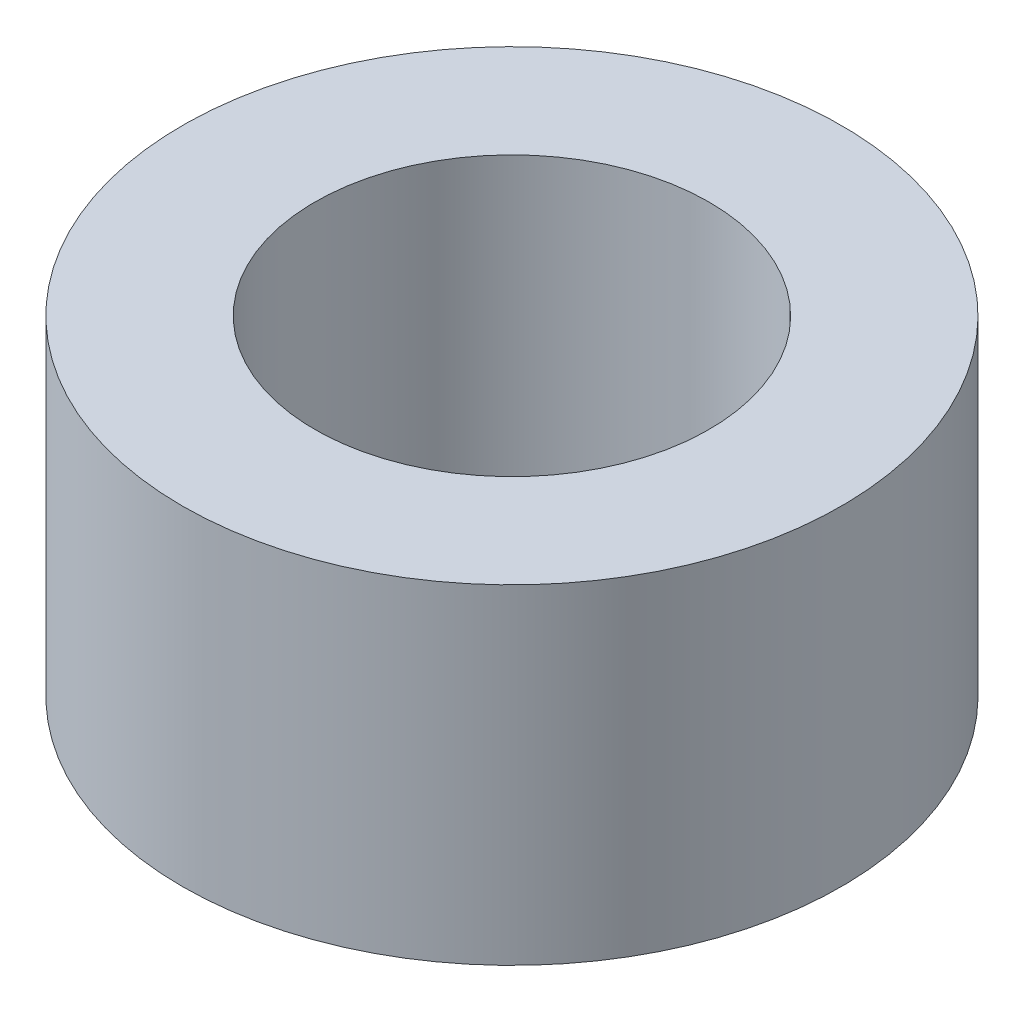
SolidWorks part; units mm, degrees
material "Nylon 101"
ref_plane "Front" through (0, 0, 0) normal (0, 0, 1) x (1, 0, 0)
ref_plane "Top" through (0, 0, 0) normal (0, 1, 0) x (1, 0, 0)
ref_plane "Right" through (0, 0, 0) normal (1, 0, 0) x (0, 0, -1)
sketch "Sketch1" plane through (0, 0, 0) normal (0, 1, 0) x (1, 0, 0)
  circle A0 centre (0, 0) radius 3.175
  dimension "D1" = 6.35
extrude "Boss-Extrude1" add sketch "Sketch1" along normal blind 3.175
sketch "Sketch3" plane through (0, 0, 0) normal (0, -1, 0) x (1, 0, 0)
  point P0 (0, 0)
hole_wizard "#6 Clearance Hole1" positions "3DSketch1" profile "Sketch4" hole size "#6" standard "ANSI Inch" end condition through all
sketch3d "3DSketch1"
  point P0 (0, 0, 0)
  point P4 (0, 0, 0)
sketch "Sketch4" plane through (0, 0, 0) normal (1, 0, 0) x (0, 0, -1)
  line L0 (0, 0) -> (0, 3.175)
  line L1 (0, 3.175) -> (1.8986, 3.175)
  line L2 (1.8986, 3.175) -> (1.8986, 0)
  line L5 (1.8986, 0) -> (0, 0)
  line L11 (0, -6.35) -> (0, 107.95) construction
  dimension "Thru Hole Dia." = 3.7973
  dimension "Thru Hole Depth" = 3.175
